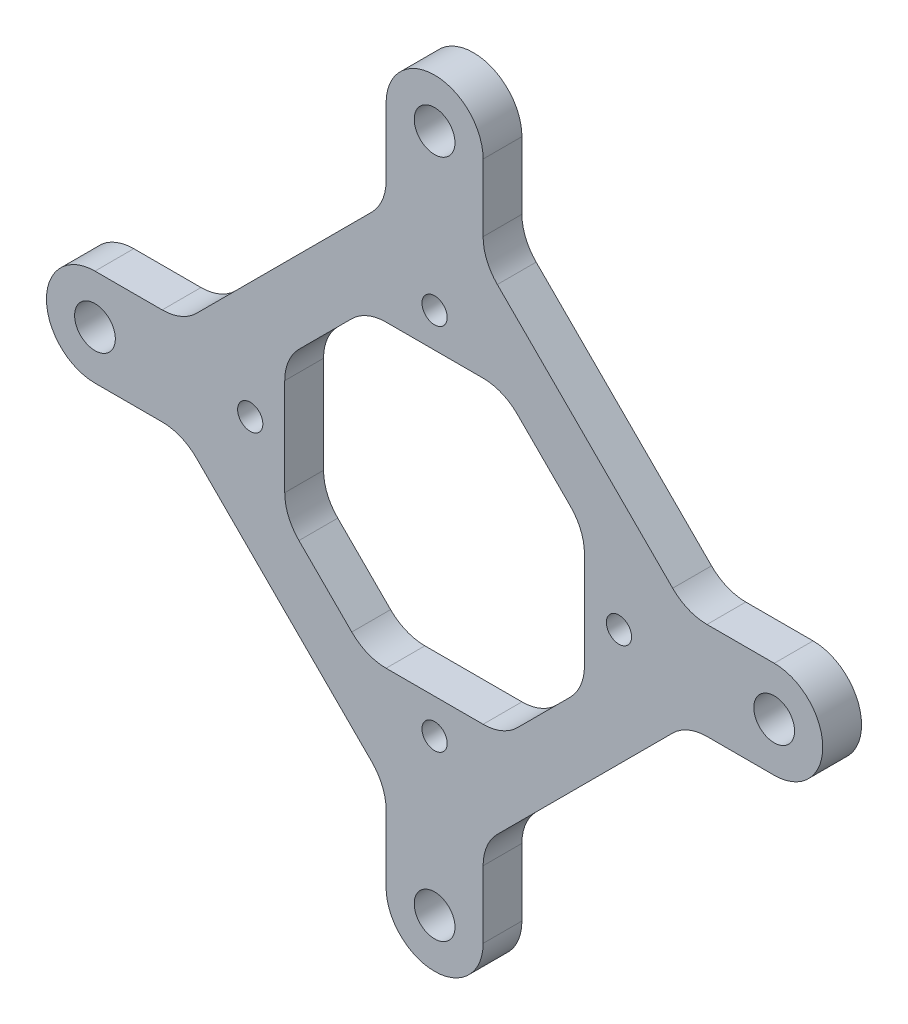
SolidWorks part; units mm, degrees
material "Thornel Mat VMA"
ref_plane "前视基准面" through (0, 0, 0) normal (0, 0, 1) x (1, 0, 0)
ref_plane "上视基准面" through (0, 0, 0) normal (0, 1, 0) x (1, 0, 0)
ref_plane "右视基准面" through (0, 0, 0) normal (1, 0, 0) x (0, 0, -1)
sketch "草图1" plane through (0, 0, 0) normal (0, 0, 1) x (1, 0, 0)
  line L0 (0, 35) -> (0, -35) construction
  line L1 (5, 35) -> (5, -35)
  line L2 (-5, 35) -> (-5, -35)
  line L3 (-35, 0) -> (35, 0) construction
  line L4 (-35, 5) -> (35, 5)
  line L5 (-35, -5) -> (35, -5)
  circle A0 centre (0, 0) radius 40 construction
  arc A1 (5, 35) -> (-5, 35) centre (0, 35) ccw
  arc A2 (-5, -35) -> (5, -35) centre (0, -35) ccw
  arc A3 (-35, 5) -> (-35, -5) centre (-35, 0) ccw
  arc A4 (35, -5) -> (35, 5) centre (35, 0) ccw
  circle A5 centre (0, 35) radius 2.1
  circle A6 centre (35, 0) radius 2.1
  circle A7 centre (0, -35) radius 2.1
  circle A8 centre (-35, 0) radius 2.1
  point P5 (0, 0)
  point P12 (0, 0)
  point P19 (35, 0)
  point P28 (0, 0)
  dimension "D1" = 80
  dimension "D4" = 4.2
  dimension "D2" = 70
  dimension "D3" = 70
  dimension "D5" = 4
extrude "凸台-拉伸1" add sketch "草图1" along normal blind 4 contours L1 A1 L2 L4 A5 | L2 A2 L1 L5 A7 | L2 L5 L1 L4 | L5 A4 L4 L1 A6 | L4 A3 L5 L2 A8
chamfer "倒角1" distance 21 angle 45 4 edges at (-5, -5, 2) (5, -5, 2) (5, 5, 2) (-5, 5, 2)
sketch "草图2" plane through (0, 0, 4) normal (0, 0, 1) x (1, 0, 0)
  line L0 (-7.0711, 15.4437) -> (-15.4437, 7.0711)
  line L1 (-15.4437, -7.0711) -> (-7.0711, -15.4437)
  line L2 (7.0711, -15.4437) -> (15.4437, -7.0711)
  line L3 (15.4437, 7.0711) -> (7.0711, 15.4437)
  line L4 (26, 5) -> (5, 26) construction
  line L5 (5, -26) -> (26, -5) construction
  line L6 (-26, -5) -> (-5, -26) construction
  line L7 (-5, 26) -> (-26, 5) construction
  line L8 (0, 0) -> (0, 19) construction
  line L9 (7.0711, 15.4437) -> (-7.0711, 15.4437)
  line L10 (15.4437, -7.0711) -> (15.4437, 7.0711)
  line L11 (-7.0711, -15.4437) -> (7.0711, -15.4437)
  line L12 (-15.4437, 7.0711) -> (-15.4437, -7.0711)
  circle A0 centre (0, 0) radius 19 construction
  circle A1 centre (0, 19) radius 1.3
  circle A2 centre (19, 0) radius 1.3
  circle A3 centre (0, -19) radius 1.3
  circle A4 centre (-19, 0) radius 1.3
  point P0 (0, 22.5147)
  point P1 (-22.5147, 0)
  point P3 (0, -22.5147)
  point P4 (22.5147, 0)
  point P17 (16.681, -16.681)
  point P18 (0, 0)
  point P19 (0, 19)
  point P26 (0, 0)
  dimension "D2" = 38
  dimension "D3" = 2.6
  dimension "D4" = 4
  dimension "D1" = 6
extrude "切除-拉伸1" cut sketch "草图2" against normal through all
fillet "圆角3" radius 5 16 edges at (-5, 26, 2) (-26, 5, 2) (-26, -5, 2) (-5, -26, 2) (5, -26, 2) (26, -5, 2) (26, 5, 2) (5, 26, 2) (15.4437, 7.0711, 2) (15.4437, -7.0711, 2) (7.0711, -15.4437, 2) (-7.0711, -15.4437, 2) (-15.4437, -7.0711, 2) (-15.4437, 7.0711, 2) (-7.0711, 15.4437, 2) (7.0711, 15.4437, 2)
